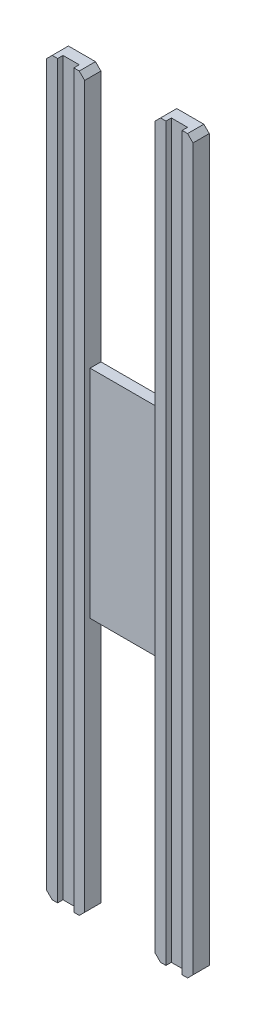
SolidWorks part; units mm, degrees
ref_plane "Piano frontale" through (0, 0, 0) normal (0, 0, 1) x (1, 0, 0)
ref_plane "Piano superiore" through (0, 0, 0) normal (0, 1, 0) x (1, 0, 0)
ref_plane "Piano destro" through (0, 0, 0) normal (1, 0, 0) x (0, 0, -1)
sketch "Schizzo1" plane through (0, 0, 0) normal (0, 0, 1) x (1, 0, 0)
  line L0 (0, 0) -> (0, 40)
  line L1 (0, 40) -> (6.5, 40)
  line L2 (6.5, 40) -> (6.5, 0)
  line L3 (6.5, 0) -> (0, 0)
  dimension "D1" = 6.5
  dimension "D2" = 40
extrude "Estrusione-Estrusione1" add sketch "Schizzo1" along normal blind 2
sketch "Schizzo2" plane through (6.5, 0, 0) normal (1, 0, 0) x (0, 0, -1)
  line L0 (0, 87.5) -> (-3, 87.5)
  line L1 (-3, 87.5) -> (-3, -47.5)
  line L2 (-3, -47.5) -> (0, -47.5)
  line L3 (0, -47.5) -> (0, 87.5)
  line L4 (0, 0) -> (0, 40) construction
  line L5 (-2, 40) -> (0, 40) construction
  dimension "D1" = 135
  dimension "D2" = 3
  dimension "D3" = 47.5
extrude "Estrusione-Estrusione2" add sketch "Schizzo2" along normal blind 7
chamfer "Smusso1" distance 1 angle 45 4 edges at (6.5, -47.5, 1.5) (13.5, -47.5, 1.5) (6.5, 87.5, 1.5) (13.5, 87.5, 1.5)
sketch "Schizzo4" plane through (0, -47.5, 0) normal (0, -1, 0) x (1, 0, 0)
  line L0 (8.5, 3) -> (8.5, 2)
  line L1 (12.5, 3) -> (7.5, 3) construction
  line L2 (8.5, 2) -> (11.5, 2)
  line L3 (11.5, 2) -> (11.5, 3)
  line L4 (11.5, 3) -> (8.5, 3)
  line L5 (6.5, 0) -> (6.5, 3) construction
  line L6 (13.5, 3) -> (13.5, 0) construction
  dimension "D1" = 2
  dimension "D2" = 2
  dimension "D3" = 1
extrude "Taglio-Estrusione1" cut sketch "Schizzo4" against normal through all
ref_plane "Piano2" through (0, 0, 0) normal (-1, 0, 0) x (0, 0, 1)
mirror "Specchia9" about plane through (0, 0, 0) normal (-1, 0, 0) of "Taglio-Estrusione1", "Estrusione-Estrusione2", "Estrusione-Estrusione1", "Smusso1"
